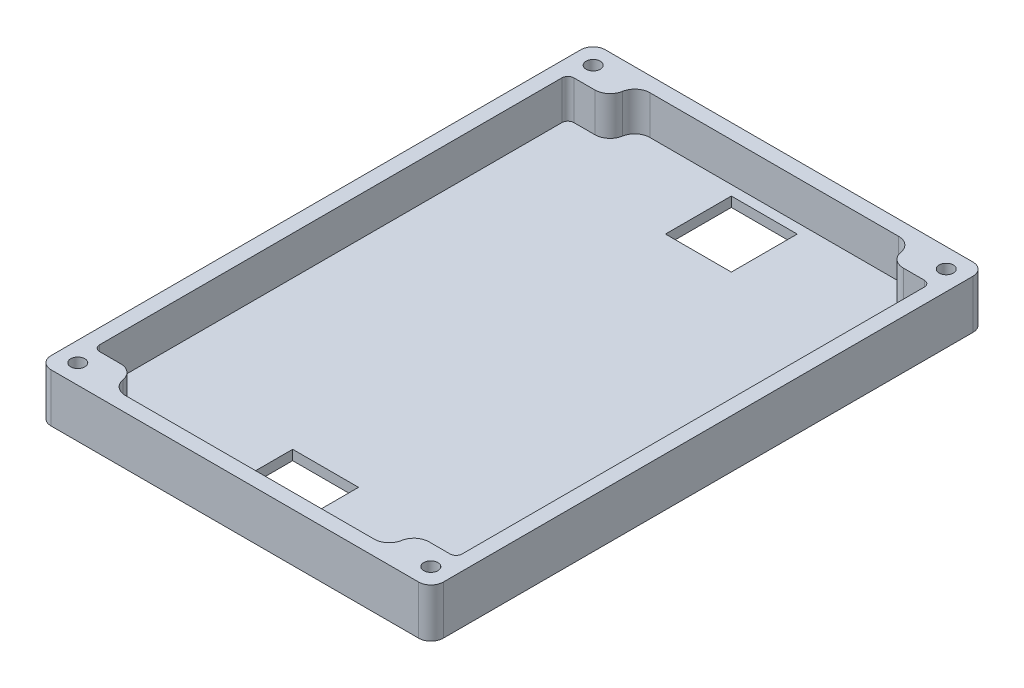
SolidWorks part; units mm, degrees
ref_plane "Front Plane" through (0, 0, 0) normal (0, 0, 1) x (1, 0, 0)
ref_plane "Top Plane" through (0, 0, 0) normal (0, 1, 0) x (1, 0, 0)
ref_plane "Right Plane" through (0, 0, 0) normal (1, 0, 0) x (0, 0, -1)
sketch "Sketch2" plane through (0, 0, 0) normal (0, 1, 0) x (1, 0, 0)
  line L1 (56.6928, -85.4964) -> (-56.6928, -85.4964)
  line L2 (60.5028, -81.6864) -> (60.5028, 81.6864)
  line L3 (56.6928, 85.4964) -> (-56.6928, 85.4964)
  line L4 (-60.5028, -81.6864) -> (-60.5028, 81.6864)
  line L5 (60.5028, -85.4964) -> (-60.5028, 85.4964) construction
  line L6 (60.5028, 85.4964) -> (-60.5028, -85.4964) construction
  arc A0 (56.6928, -85.4964) -> (60.5028, -81.6864) centre (56.6928, -81.6864) ccw
  arc A1 (60.5028, 81.6864) -> (56.6928, 85.4964) centre (56.6928, 81.6864) ccw
  arc A2 (-56.6928, 85.4964) -> (-60.5028, 81.6864) centre (-56.6928, 81.6864) ccw
  arc A3 (-56.6928, -85.4964) -> (-60.5028, -81.6864) centre (-56.6928, -81.6864) cw
  point P0 (0, 0)
  dimension "D3" = 3.81
  dimension "D1" = 121.0056
  dimension "D2" = 170.9928
extrude "Boss-Extrude1" add sketch "Sketch2" along normal blind 15.0114 contours L4 A2 L3 A1 L2 A0 L1 A3
sketch "Sketch3" plane through (0, 15.0114, 0) normal (0, 1, 0) x (1, 0, 0)
  line L0 (0, -45.4066) -> (0, 125.5862) construction
  line L1 (42.9274, 0) -> (-42.9274, 0) construction
  line L2 (-55.9054, 0) -> (-55.9054, 71.2945)
  line L3 (-54.0479, 73.152) -> (-47.5539, 73.152)
  line L4 (-38.3709, 80.899) -> (0, 80.899)
  line L5 (-55.9054, 0) -> (0, 0)
  line L6 (0, 0) -> (0, 80.899)
  line L9 (-60.5028, -81.6864) -> (-60.5028, 81.6864) construction
  line L10 (56.6928, 85.4964) -> (-56.6928, 85.4964) construction
  arc A0 (-55.9054, 71.2945) -> (-54.0479, 73.152) centre (-54.0479, 71.2945) cw
  arc A1 (-47.5539, 73.152) -> (-42.9624, 77.0255) centre (-47.5539, 77.81) ccw
  arc A2 (-42.9624, 77.0255) -> (-38.3709, 80.899) centre (-38.3709, 76.241) cw
  dimension "D1" = 4.5974
  dimension "D2" = 4.5974
  dimension "D3" = 73.152
extrude "Cut-Extrude1" cut sketch "Sketch3" against normal blind 11.9634
mirror "Mirror1" about plane through (0, 0, 0) normal (1, 0, 0) of "Cut-Extrude1"
mirror "Mirror2" about plane through (0, 0, 0) normal (0, 0, 1) of "Mirror1", "Cut-Extrude1"
hole_wizard "CBORE SLOT for #3 Binding Head Machine Screw1" positions "Sketch6" profile "Sketch7" size "#3" standard "ANSI Inch" slot yes
sketch "Sketch6" plane through (0, 0, 0) normal (0, -1, 0) x (-1, 0, 0)
  point P0 (-54.4576, 79.502)
  dimension "D1" = 54.4576
  dimension "D2" = 79.502
sketch "Sketch7" plane through (54.4576, 0, -79.502) normal (1, 0, 0) x (0, 0, -1)
  line L0 (0, 0) -> (0, 15.0114)
  line L1 (0, 15.0114) -> (2.1844, 15.0114)
  line L2 (2.1844, 15.0114) -> (2.1844, 3.048)
  line L3 (2.1844, 3.048) -> (3.937, 3.048)
  line L4 (3.937, 3.048) -> (3.937, 0)
  line L5 (3.937, 0) -> (0, 0)
  line L10 (0, 15.0114) -> (-2.1844, 15.0114) construction
  line L11 (0, -6.35) -> (0, 107.95) construction
  dimension "Hole Dia." = 4.3688
  dimension "Hole Depth" = 15.0114
  dimension "C'Bore Dia." = 7.874
  dimension "C'Bore Depth" = 3.048
  dimension "Drill Angle" = 180
mirror "Mirror3" about plane through (0, 0, 0) normal (1, 0, 0) of "CBORE SLOT for #3 Binding Head Machine Screw1"
mirror "Mirror4" about plane through (0, 0, 0) normal (0, 0, 1) of "Mirror3", "CBORE SLOT for #3 Binding Head Machine Screw1"
sketch "Sketch10" plane through (0, 0, 0) normal (0, -1, 0) x (1, 0, 0)
  line L1 (10.16, 57.5) -> (-10.16, 57.5)
  line L2 (10.16, 57.5) -> (10.16, 77.82)
  line L3 (10.16, 77.82) -> (-10.16, 77.82)
  line L4 (-10.16, 57.5) -> (-10.16, 77.82)
  line L5 (0, 77.82) -> (0, -2.95) construction
  dimension "D1" = 20.32
  dimension "D2" = 20.32
extrude "Cut-Extrude3" cut sketch "Sketch10" against normal up to surface (3.048 mm away) up to face at (0, 3.048, 0)
mirror "Mirror7" about plane through (0, 0, 0) normal (0, 0, 1) of "Cut-Extrude3"
